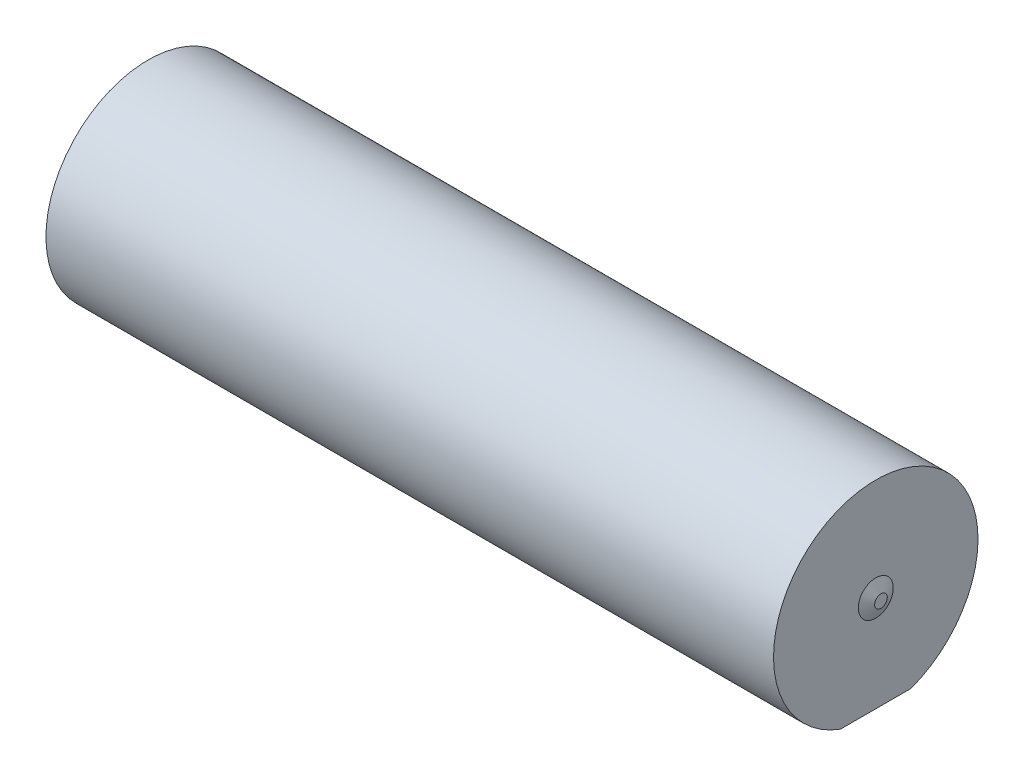
SolidWorks part; units mm, degrees
ref_plane "Front Plane" through (0, 0, 0) normal (0, 0, 1) x (1, 0, 0)
ref_plane "Top Plane" through (0, 0, 0) normal (0, 1, 0) x (1, 0, 0)
ref_plane "Right Plane" through (0, 0, 0) normal (1, 0, 0) x (0, 0, -1)
sketch "Çizim1" plane through (0, 0, 0) normal (0, 0, 1) x (1, 0, 0)
  line L0 (0, 160) -> (800, 160)
  line L1 (0, 160) -> (0, 196.6455)
  line L2 (0, 196.6455) -> (1399.3195, 196.6455)
  line L3 (1399.3195, 196.6455) -> (1399.3195, 9.4748)
  line L4 (0, 0) -> (1371.0396, 0) construction
  arc A0 (800, 160) -> (1399.3195, 9.4748) centre (800, -1108.3649) cw
  dimension "D1" = 800
  dimension "D3" = 160
revolve "Döndür2" add sketch "Çizim1" angle 360 about L4
sketch "Çizim2" plane through (0, 0, 0) normal (0, 0, 1) x (1, 0, 0)
  line L13 (0, 0) -> (167.3497, 0) construction
  line L14 (0, 196.6455) -> (0, -196.6455) construction
  line L15 (0, 0) -> (1371.0396, 0) construction
  line L17 (1389.3195, 26.0598) -> (1389.3195, 186.6455)
  line L18 (10, 170) -> (800, 170)
  line L19 (10, 186.6455) -> (10, 170)
  line L20 (1389.3195, 186.6455) -> (10, 186.6455)
  line L21 (1389.3195, 26.0598) -> (1389.3195, 186.6455)
  line L22 (-316.1342, 170) -> (800, 170)
  line L23 (-316.1342, 186.6455) -> (-316.1342, 170)
  line L24 (1389.3195, 186.6455) -> (-316.1342, 186.6455)
  arc A3 (1389.3195, 26.0598) -> (800, 170) centre (800, -1108.3649) ccw
  arc A4 (1389.3195, 26.0598) -> (800, 170) centre (800, -1108.3649) ccw
  dimension "D1" = 10
revolve "Kes-Döndür1" cut sketch "Çizim2" angle 360 about L13
sketch "Çizim3" plane through (1399.3195, 0, 0) normal (1, 0, 0) x (0, 0, -1)
  circle A0 centre (0, 0) radius 33.5796
extrude "Yükseklik-Ekstrüzyon1" add sketch "Çizim3" along normal blind 10 draft 65
scale "Ölçek2" scale about centroid uniform scaling yes scale factor 1
sketch "Çizim4" plane through (0, 0, 0) normal (1, 0, 0) x (0, 0, -1)
  line L0 (97.1768, -191.2177) -> (-137.7329, -191.2177)
  line L1 (97.1768, -191.2177) -> (64.6159, -223.7785)
  line L2 (64.6159, -223.7785) -> (-99.9777, -250.956)
  line L3 (-99.9777, -250.956) -> (-137.7329, -191.2177)
extrude "Kes-Ekstrüzyon1" cut sketch "Çizim4" along normal blind 436 from offset 1000
sketch "Çizim5" plane through (1000, 0, 0) normal (1, 0, 0) x (0, 0, -1)
  line L0 (-78.2432, -184.5949) -> (94.8343, -184.5949)
  line L1 (94.8343, -184.5949) -> (68.7093, -210.7198)
  line L2 (68.7093, -210.7198) -> (-83.6859, -208.1798)
  line L3 (-83.6859, -208.1798) -> (-78.2432, -184.5949)
extrude "Kes-Ekstrüzyon2" cut sketch "Çizim5" along normal blind 729
